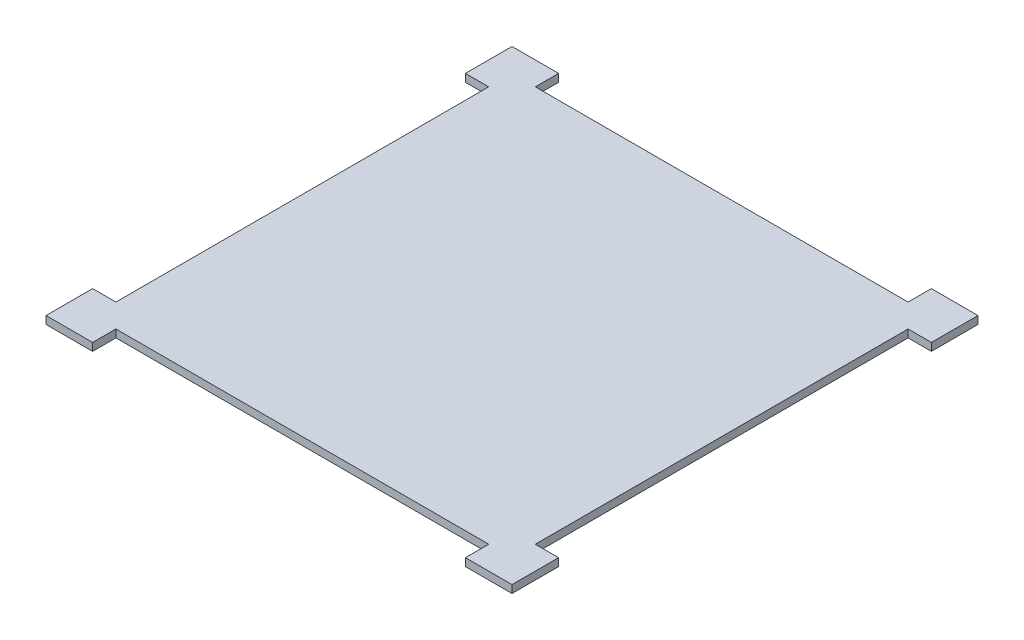
SolidWorks part; units mm, degrees
ref_plane "前视基准面" through (0, 0, 0) normal (0, 0, 1) x (1, 0, 0)
ref_plane "上视基准面" through (0, 0, 0) normal (0, 1, 0) x (1, 0, 0)
ref_plane "右视基准面" through (0, 0, 0) normal (1, 0, 0) x (0, 0, -1)
sketch "草图1" plane through (0, 0, 0) normal (0, 1, 0) x (1, 0, 0)
  line L1 (-135, -135) -> (135, -135)
  line L2 (-135, -135) -> (-135, 135)
  line L3 (-135, 135) -> (135, 135)
  line L4 (135, -135) -> (135, 135)
  line L5 (-135, -135) -> (135, 135) construction
  line L6 (-135, 135) -> (135, -135) construction
  circle A0 centre (0, 0) radius 110
  circle A1 centre (0, 0) radius 125
  circle A2 centre (-88.3883, -88.3883) radius 2.5
  circle A3 centre (-88.3883, 88.3883) radius 2.5
  circle A4 centre (88.3883, 88.3883) radius 2.5
  circle A5 centre (88.3883, -88.3883) radius 2.5
  point P0 (0, 0)
  point P11 (0, 0)
  point P12 (63.8207, -83.2449)
  point P13 (-351.3398, 84.1723)
  point P20 (0, 0)
  dimension "D2" = 220
  dimension "D4" = 250
  dimension "D5" = 5
  dimension "D1" = 270
  dimension "D3" = 270
  dimension "D6" = 4
sketch "草图2" plane through (0, 0, 0) normal (0, 1, 0) x (1, 0, 0)
  line L0 (-120, -150) -> (-120, -135)
  line L1 (-120, -135) -> (120, -135)
  line L2 (-135, -120) -> (-135, 120)
  line L3 (-120, 135) -> (120, 135)
  line L4 (135, -120) -> (135, 120)
  line L5 (-150, -150) -> (-120, -150)
  line L6 (-150, -150) -> (-150, -120)
  line L9 (-150, -150) -> (-120, -120) construction
  line L10 (-150, -120) -> (-120, -150) construction
  line L11 (-150, -120) -> (-135, -120)
  line L12 (-150, 150) -> (-150, 120)
  line L13 (-150, 120) -> (-135, 120)
  line L14 (-150, 150) -> (-120, 150)
  line L15 (-120, 150) -> (-120, 135)
  line L16 (150, 150) -> (120, 150)
  line L17 (120, 150) -> (120, 135)
  line L18 (150, 150) -> (150, 120)
  line L19 (150, 120) -> (135, 120)
  line L20 (150, -150) -> (150, -120)
  line L21 (150, -120) -> (135, -120)
  line L22 (150, -150) -> (120, -150)
  line L23 (120, -150) -> (120, -135)
  point P30 (0, 0)
  dimension "D1" = 30
  dimension "D2" = 30
  dimension "D3" = 4
extrude "凸台-拉伸1" add sketch "草图2" along normal blind 5
sketch "草图3" plane through (0, 0, 0) normal (0, 1, 0) x (1, 0, 0)
  circle A0 centre (-88.3883, 88.3883) radius 2.5 construction
  circle A1 centre (-88.3883, 88.3883) radius 2.5
  circle A2 centre (88.3883, 88.3883) radius 2.5 construction
  circle A3 centre (88.3883, 88.3883) radius 2.5
  circle A4 centre (-88.3883, -88.3883) radius 2.5 construction
  circle A5 centre (-88.3883, -88.3883) radius 2.5
  circle A6 centre (88.3883, -88.3883) radius 2.5 construction
  circle A7 centre (88.3883, -88.3883) radius 2.5
extrude "凸台-拉伸2" add sketch "草图3" against normal blind 5
